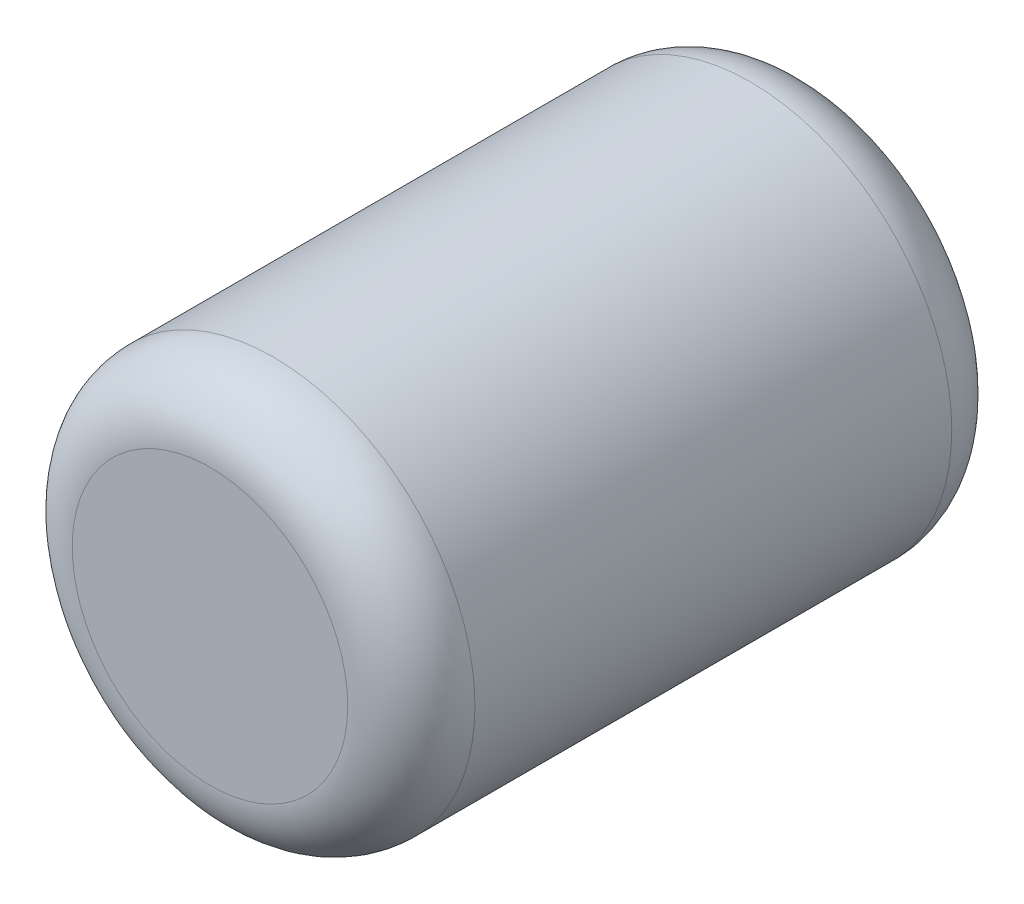
SolidWorks part; units mm, degrees
ref_plane "Front Plane" through (0, 0, 0) normal (0, 0, 1) x (1, 0, 0)
ref_plane "Top Plane" through (0, 0, 0) normal (0, 1, 0) x (1, 0, 0)
ref_plane "Right Plane" through (0, 0, 0) normal (1, 0, 0) x (0, 0, -1)
sketch "Sketch2" plane through (0, 0, 0) normal (0, 0, 1) x (1, 0, 0)
  circle A0 centre (0, 0) radius 9.5
  dimension "D1" = 19
extrude "Boss-Extrude1" add sketch "Sketch2" along normal blind 28.5
ref_point "Point1"
ref_point "Point2"
fillet "Fillet1" radius 3 2 edges at (9.5, 0, 28.5) (9.5, 0, 0)
